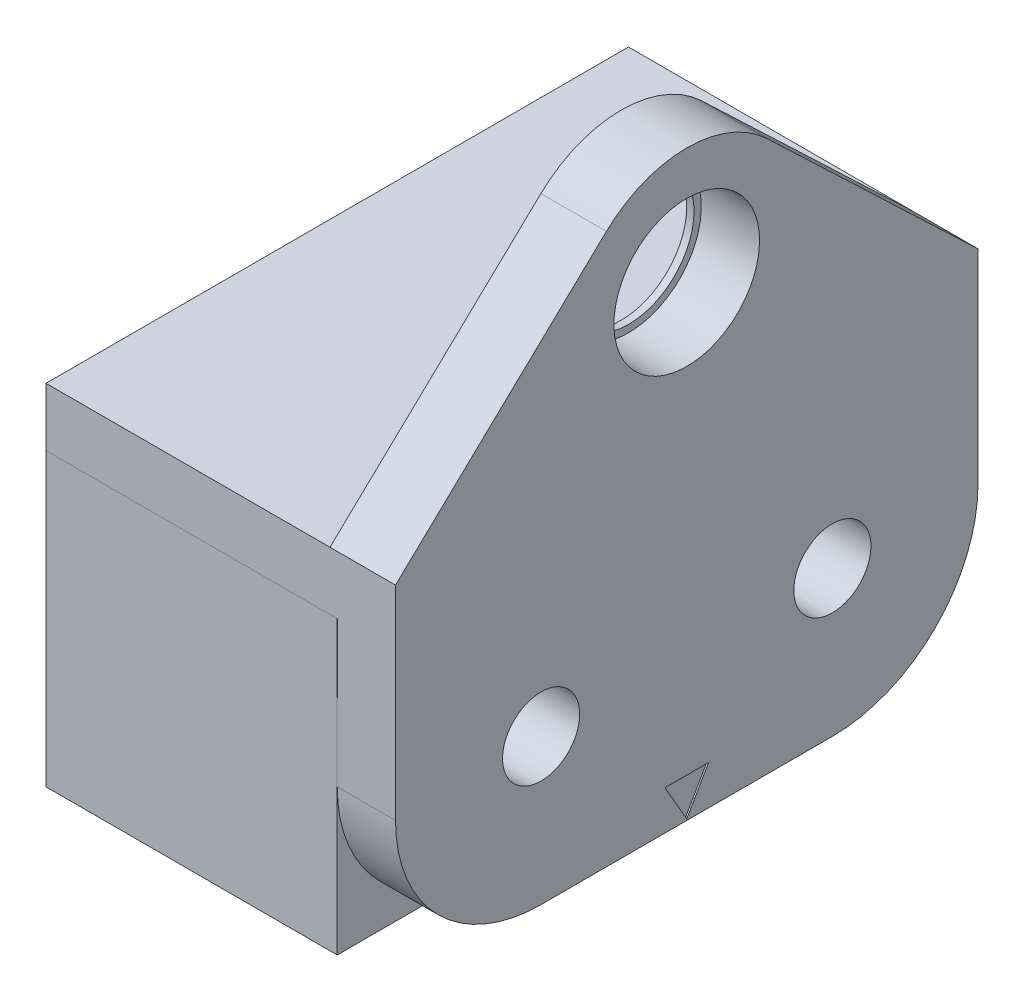
SolidWorks part; units mm, degrees
material "ABS"
ref_plane "Спереди" through (0, 0, 0) normal (0, 0, 1) x (1, 0, 0)
ref_plane "Сверху" through (0, 0, 0) normal (0, 1, 0) x (1, 0, 0)
ref_plane "Справа" through (0, 0, 0) normal (1, 0, 0) x (0, 0, -1)
sketch "Эскиз2" plane through (0, 0, 0) normal (0, 0, 1) x (1, 0, 0)
  line L1 (10, -10) -> (-10, -10)
  line L2 (10, -10) -> (10, 10)
  line L3 (10, 10) -> (-10, 10)
  line L4 (-10, -10) -> (-10, 10)
  line L5 (10, -10) -> (-10, 10) construction
  line L6 (10, 10) -> (-10, -10) construction
  point P0 (0, 0)
  dimension "D1" = 20
  dimension "D2" = 20
extrude "Бобышка-Вытянуть1" add sketch "Эскиз2" along normal mid plane 40
sketch "Эскиз3" plane through (10, 0, 0) normal (1, 0, 0) x (0, 0, -1)
  line L1 (-20, 10) -> (20, 10)
  line L2 (-20, 10) -> (20, 10) construction
  line L3 (-20, 10) -> (-20, 14)
  line L4 (-20, 14) -> (20, 14)
  line L5 (-20, 10) -> (20, 10)
  line L6 (20, 10) -> (20, 14)
  line L7 (20, -10) -> (20, 10)
  line L8 (20, 10) -> (-20, 10)
  line L9 (-20, 10) -> (-20, -10)
  line L10 (-20, -10) -> (20, -10)
  line L11 (20, -10) -> (20, 10)
  line L12 (0, 14) -> (0, 10) construction
  line L13 (-20, 10) -> (-20, -10)
  line L14 (-20, -10) -> (20, -10)
  line L15 (-20, 12) -> (20, 12) construction
  point P224 (0, 12)
  dimension "D1" = 4
  dimension "D3" = 0
extrude "Бобышка-Вытянуть2" add sketch "Эскиз3" along normal blind 4 separate body
hole_wizard "Отверстие с зазором M51" positions "Эскиз4" profile "Эскиз5" hole size "M5" standard "ISO" end condition up to next
sketch "Эскиз4" plane through (14, 0, 0) normal (1, 0, 0) x (0, 0, -1)
  point P0 (-10, 0)
  point P2 (10, 0)
  dimension "D1" = 20
  dimension "D2" = 10
sketch "Эскиз5" plane through (14, 0, 10) normal (0, 1, 0) x (0, 0, -1)
  line L0 (0, 0) -> (0, 24)
  line L1 (0, 24) -> (2.65, 24)
  line L2 (2.65, 24) -> (2.65, 0)
  line L5 (2.65, 0) -> (0, 0)
  line L11 (0, -6.35) -> (0, 107.95) construction
  dimension "Диаметр сквозного отверстия" = 5.3
  dimension "Глубина сквозного отверстия" = 24
sketch "Эскиз6" plane through (10, 0, 0) normal (-1, 0, 0) x (0, 0, 1)
  line L0 (-20, -10) -> (-20, 14) construction
  line L1 (20, 14) -> (-20, 14)
  line L3 (20, 14) -> (20, 10)
  line L5 (20, 10) -> (-20, 10)
  line L6 (-20, 14) -> (-20, 10)
  line L7 (0, 10) -> (0, 14) construction
  line L8 (20, 12) -> (-20, 12) construction
  point P242 (0, 12)
  dimension "D1" = 4
extrude "Бобышка-Вытянуть3" add sketch "Эскиз6" along normal blind 20
sketch "Эскиз7" plane through (0, 10, 0) normal (0, -1, 0) x (1, 0, 0)
  line L0 (0, 0) -> (-50000, 0) construction
  line L1 (-3.05, 8) -> (3.05, 8)
  line L2 (-3.05, 8) -> (-3.05, 16)
  line L3 (-3.05, 16) -> (3.05, 16)
  line L4 (3.05, 8) -> (3.05, 16)
  line L5 (0, 16) -> (0, 8) construction
  line L6 (-3.05, 12) -> (3.05, 12) construction
  line L7 (-3.05, -12) -> (3.05, -12) construction
  line L8 (0, -16) -> (0, -8) construction
  line L9 (3.05, -8) -> (3.05, -16)
  line L10 (-3.05, -16) -> (3.05, -16)
  line L11 (-3.05, -8) -> (-3.05, -16)
  line L12 (-3.05, -8) -> (3.05, -8)
  point P14 (0, -12)
  point P56 (0, 12)
  dimension "D1" = 6.1
  dimension "D2" = 8
  dimension "D3" = 12
extrude "Бобышка-Вытянуть4" add sketch "Эскиз7" along normal blind 3
chamfer "Фаска1" distance 1 angle 45 4 edges at (-3.05, 7, 12) (3.05, 7, 12) (3.05, 7, -12) (-3.05, 7, -12)
sketch "Эскиз8" plane through (14, 0, 0) normal (1, 0, 0) x (0, 0, -1)
  line L0 (-20, 14) -> (-5.5172, 27.7931)
  line L1 (5.5172, 27.7931) -> (20, 14)
  line L2 (-20, 14) -> (20, 14) construction
  circle A0 centre (0, 22) radius 5
  arc A1 (-5.5172, 27.7931) -> (5.5172, 27.7931) centre (0, 22) cw
  line M8 (20, 14) -> (-20, 14)
  dimension "D1" = 10
  dimension "D2" = 3
  dimension "D3" = 3
extrude "Бобышка-Вытянуть5" add sketch "Эскиз8" against normal blind 4.5 contours A1 L0 L1 A0 M8
sketch "Эскиз9" plane through (9.5, 0, 0) normal (-1, 0, 0) x (0, 0, 1)
  circle A0 centre (0, 22) radius 5 construction
  circle A1 centre (0, 22) radius 5
  circle A2 centre (0, 22) radius 4.5
  dimension "D1" = 0.5
extrude "Бобышка-Вытянуть6" add sketch "Эскиз9" against normal offset from surface (0.5 mm away) 4 up to face at (14, 0, 7.35)
fillet "Скругление1" radius 10 2 edges at (12, -10, 20) (12, -10, -20)
sketch "Эскиз10" plane through (14, 0, 0) normal (1, 0, 0) x (0, 0, -1)
  line L0 (0, -9.9) -> (1.5, -7.3019)
  line L2 (1.5, -7.3019) -> (-1.5, -7.3019)
  line L3 (-1.5, -7.3019) -> (0, -9.9)
  line L4 (-10, -10) -> (10, -10) construction
  point P2 (0, -9.0099)
  dimension "D1" = 3
  dimension "D2" = 0.1
extrude "Вырез-Вытянуть2" cut sketch "Эскиз10" against normal blind 0.1 contours L2 L3 L0
